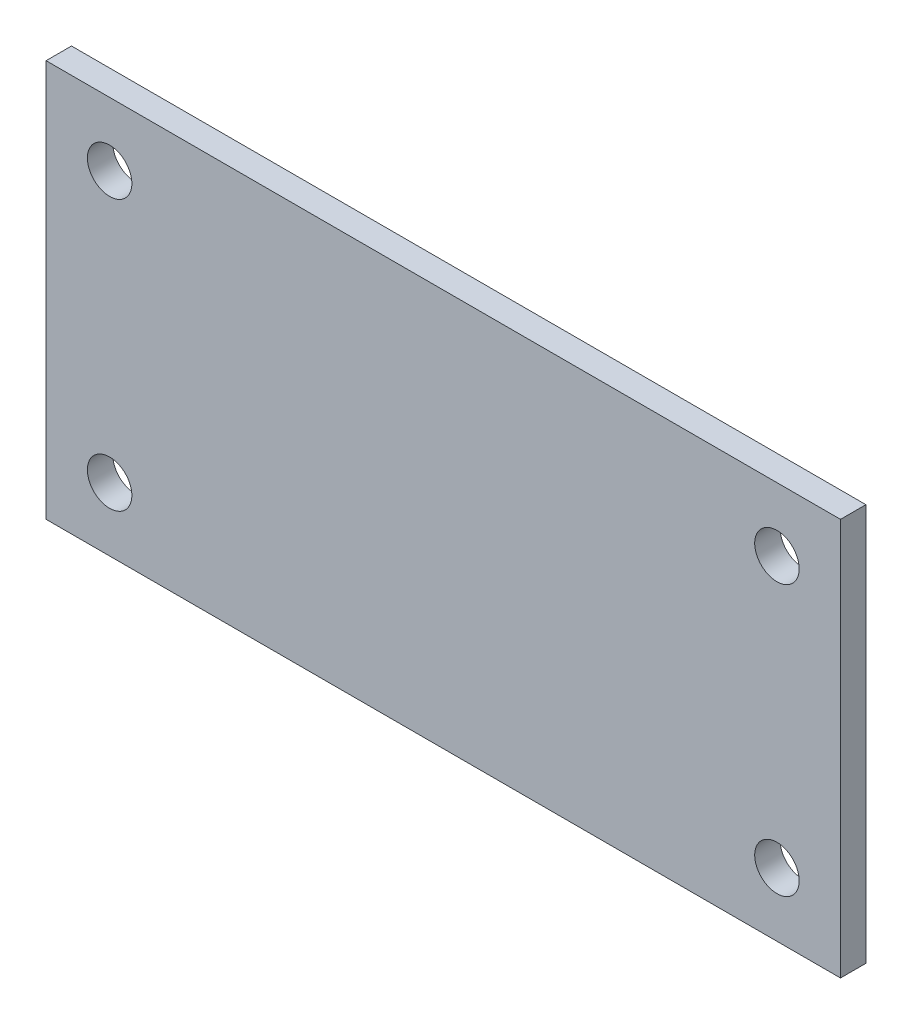
SolidWorks part; units mm, degrees
ref_plane "Front Plane" through (0, 0, 0) normal (0, 0, 1) x (1, 0, 0)
ref_plane "Top Plane" through (0, 0, 0) normal (0, 1, 0) x (1, 0, 0)
ref_plane "Right Plane" through (0, 0, 0) normal (1, 0, 0) x (0, 0, -1)
other "Configuration Table"
sketch "Sketch2" plane through (0, 0, 0) normal (0, 0, 1) x (1, 0, 0)
  line L1 (-25, -12.5) -> (25, -12.5)
  line L2 (-25, -12.5) -> (-25, 12.5)
  line L3 (-25, 12.5) -> (25, 12.5)
  line L4 (25, -12.5) -> (25, 12.5)
extrude "Generic_ESP32_carrier_reference" add sketch "Sketch2" along normal blind 1.6 from offset 0
sketch "Sketch3" plane through (0, 0, 0) normal (0, 0, 1) x (1, 0, 0)
  circle A0 centre (-21, -8.5) radius 1.4
  circle A1 centre (-21, 8.5) radius 1.4
  circle A2 centre (21, -8.5) radius 1.4
  circle A3 centre (21, 8.5) radius 1.4
extrude "Four_M2p5_clearance_holes" cut sketch "Sketch3" along normal through all
